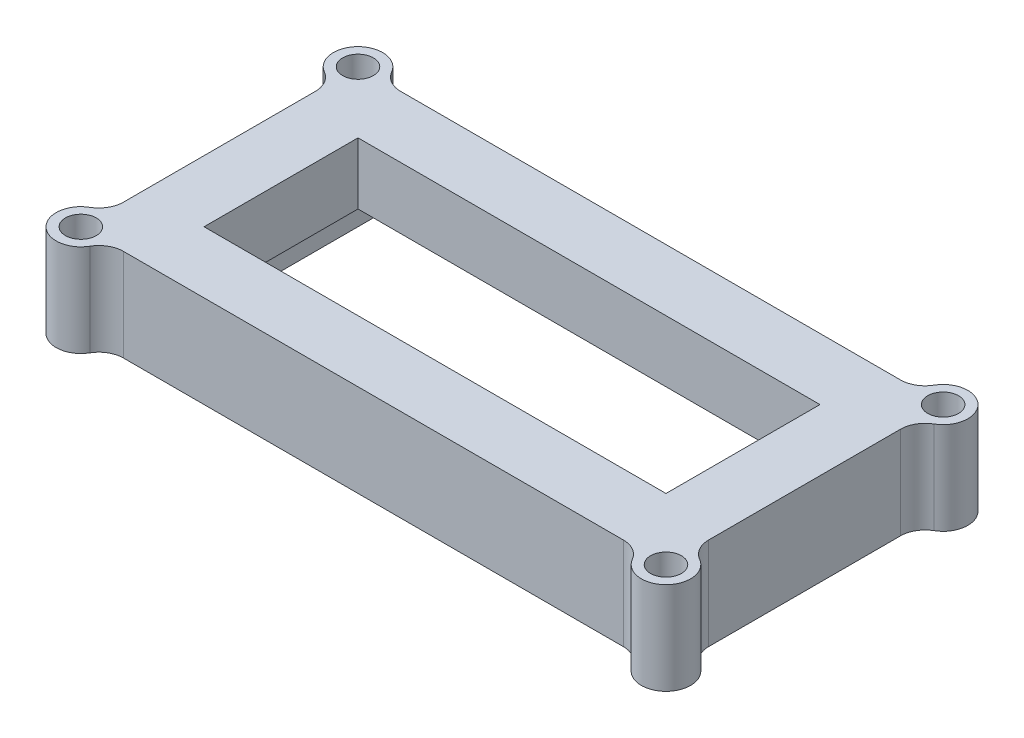
SolidWorks part; units mm, degrees
ref_plane "Front Plane" through (0, 0, 0) normal (0, 0, 1) x (1, 0, 0)
ref_plane "Top Plane" through (0, 0, 0) normal (0, 1, 0) x (1, 0, 0)
ref_plane "Right Plane" through (0, 0, 0) normal (1, 0, 0) x (0, 0, -1)
sketch "Sketch2" plane through (0, 0, 0) normal (0, 1, 0) x (1, 0, 0)
  line L0 (0, 0) -> (0, 33.7204) construction
  line L1 (-47.5, 22.5) -> (47.5, 22.5)
  line L2 (-47.5, 22.5) -> (-47.5, -22.5)
  line L3 (-47.5, -22.5) -> (47.5, -22.5)
  line L4 (47.5, 22.5) -> (47.5, -22.5)
  line L5 (-47.5, 22.5) -> (47.5, -22.5) construction
  line L6 (-47.5, -22.5) -> (47.5, 22.5) construction
  line L7 (-37.5, 12.5) -> (37.5, 12.5)
  line L8 (-37.5, 12.5) -> (-37.5, -12.5)
  line L9 (-37.5, -12.5) -> (37.5, -12.5)
  line L10 (37.5, 12.5) -> (37.5, -12.5)
  line L11 (-37.5, 12.5) -> (37.5, -12.5) construction
  line L12 (-37.5, -12.5) -> (37.5, 12.5) construction
  line L13 (0, 0) -> (-56.7787, 0) construction
  circle A0 centre (-47.5, 22.5) radius 4
  circle A1 centre (-47.5, 22.5) radius 1.5
  circle A2 centre (-47.5, -22.5) radius 1.5
  circle A3 centre (-47.5, -22.5) radius 4
  circle A4 centre (47.5, 22.5) radius 4
  circle A5 centre (47.5, -22.5) radius 1.5
  circle A6 centre (47.5, -22.5) radius 4
  circle A7 centre (47.5, 22.5) radius 1.5
  point P0 (0, 0)
  point P6 (0, 0)
  dimension "D5" = 3
  dimension "D6" = 8
  dimension "D1" = 75
  dimension "D2" = 25
  dimension "D3" = 10
  dimension "D4" = 10
extrude "Boss-Extrude1" add sketch "Sketch2" along normal blind 15 contours L4 A7 L1 A4 | L1 A7 L4 A4 | L3 A6 L4 A5 | L4 A6 L3 A5 | A3 L2 A2 L3 | A3 L3 A2 L2 | A1 L2 A0 L1 | A1 L1 A0 L2 | A6 L4 A4 L1 A0 L2 A3 L3 L7 L10 L9 L8
fillet "Fillet3" radius 4 1 edges at (-43.5, 7.5, -22.5)
fillet "Fillet4" radius 4 1 edges at (-47.5, 7.5, -18.5)
fillet "Fillet5" radius 4 1 edges at (47.5, 7.5, -18.5)
fillet "Fillet6" radius 4 1 edges at (43.5, 7.5, -22.5)
fillet "Fillet7" radius 4 1 edges at (47.5, 7.5, 18.5)
fillet "Fillet8" radius 4 1 edges at (43.5, 7.5, 22.5)
fillet "Fillet9" radius 4 1 edges at (-43.5, 7.5, 22.5)
fillet "Fillet10" radius 4 1 edges at (-47.5, 7.5, 18.5)
sketch "Sketch3" plane through (0, 15, 0) normal (0, 1, 0) x (1, 0, 0)
  circle A0 centre (-47.5, 22.5) radius 2.5
  circle A1 centre (47.5, 22.5) radius 2.5
  circle A2 centre (47.5, -22.5) radius 2.5
  circle A3 centre (-47.5, -22.5) radius 2.5
  dimension "D1" = 5
  dimension "D2" = 5
  dimension "D3" = 5
  dimension "D4" = 5
extrude "Cut-Extrude1" cut sketch "Sketch3" against normal blind 10
sketch "Sketch5" plane through (0, 0, 0) normal (0, -1, 0) x (-1, 0, 0)
  line L1 (40, -18) -> (-40, -18)
  line L2 (40, -18) -> (40, 18)
  line L3 (40, 18) -> (-40, 18)
  line L4 (-40, -18) -> (-40, 18)
  line L5 (40, -18) -> (-40, 18) construction
  line L6 (40, 18) -> (-40, -18) construction
  point P0 (0, 0)
  dimension "D1" = 80
  dimension "D2" = 36
extrude "Cut-Extrude2" cut sketch "Sketch5" against normal blind 5
